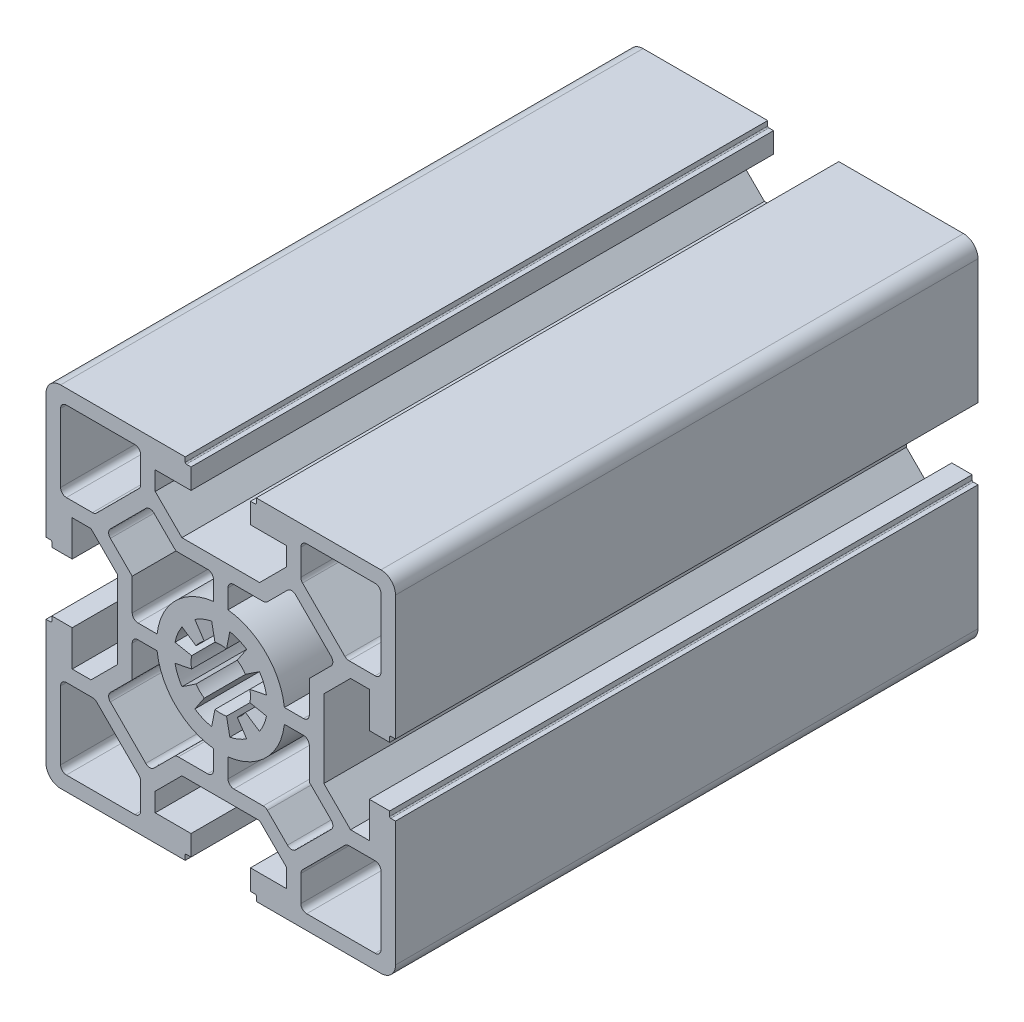
SolidWorks part; units mm, degrees
ref_plane "前视基准面" through (0, 0, 0) normal (0, 0, 1) x (1, 0, 0)
ref_plane "上视基准面" through (0, 0, 0) normal (0, 1, 0) x (1, 0, 0)
ref_plane "右视基准面" through (0, 0, 0) normal (1, 0, 0) x (0, 0, -1)
sketch "草图1" plane through (0, 0, 0) normal (0, 0, 1) x (1, 0, 0)
  line L0 (-4.4632, 29.8486) -> (-25.8632, 29.8486)
  line L1 (-28.3632, 27.3486) -> (-28.3632, 5.9486)
  line L2 (-24.8632, 13.5986) -> (-20.3827, 13.5986)
  line L3 (-19.6756, 13.8915) -> (-12.4061, 21.161)
  line L4 (-12.1132, 21.8682) -> (-12.1132, 26.3486)
  line L5 (-13.1132, 27.3486) -> (-24.8632, 27.3486)
  line L6 (-25.8632, 26.3486) -> (-25.8632, 14.5986)
  line L7 (1.6368, 17.5486) -> (-5.0323, 17.5486)
  line L8 (0.3868, 10.7773) -> (0.3868, 14.0486)
  line L9 (-0.6132, 15.0486) -> (-5.6536, 15.0486)
  line L10 (-6.3607, 15.3415) -> (-9.8183, 18.7991)
  line L11 (-16.0632, 6.5177) -> (-16.0632, -0.1514)
  line L12 (-13.5632, 7.5533) -> (-13.5632, 2.0986)
  line L13 (-12.5632, 1.0986) -> (-9.2919, 1.0986)
  line L14 (-3.4632, 25.3486) -> (-9.6132, 25.3486)
  line L15 (-23.8632, 11.0986) -> (-23.8632, 4.9486)
  line L16 (-3.4632, 28.8486) -> (-4.2632, 28.8486)
  line L17 (-4.4632, 29.0486) -> (-4.4632, 29.8486)
  line L18 (-28.3632, 5.9486) -> (-27.5632, 5.9486)
  line L19 (-27.3632, 5.7486) -> (-27.3632, 4.9486)
  line L20 (-23.8632, 11.0986) -> (-20.644, 11.0986)
  line L21 (-27.3632, 4.9486) -> (-23.8632, 4.9486)
  line L22 (-9.6132, 25.3486) -> (-9.6132, 22.1295)
  line L23 (-3.4632, 28.8486) -> (-3.4632, 25.3486)
  line L24 (-2.8077, -6.8032) -> (-1.1966, -4.3919)
  line L25 (0.0761, -7.9977) -> (0.6419, -5.1534)
  line L26 (3.1975, -7.9977) -> (2.6318, -5.1534)
  line L27 (6.0814, -6.8032) -> (4.4702, -4.3919)
  line L28 (8.2886, -4.596) -> (5.8773, -2.9848)
  line L29 (9.4831, -1.7121) -> (6.6388, -1.1464)
  line L30 (9.4831, 1.4093) -> (6.6388, 0.8436)
  line L31 (8.2886, 4.2932) -> (5.8773, 2.682)
  line L32 (6.0814, 6.5004) -> (4.4702, 4.0891)
  line L33 (3.1975, 7.6949) -> (2.6318, 4.8506)
  line L34 (0.0761, 7.6949) -> (0.6419, 4.8506)
  line L35 (-2.8077, 6.5004) -> (-1.1966, 4.0891)
  line L36 (-5.0149, 4.2932) -> (-2.6037, 2.682)
  line L37 (-6.2095, 1.4093) -> (-3.3652, 0.8436)
  line L38 (-6.2095, -1.7121) -> (-3.3652, -1.1464)
  line L39 (-5.0149, -4.596) -> (-2.6037, -2.9848)
  line L40 (-20.644, 11.0986) -> (-16.0632, 6.5177)
  line L41 (-17.3136, 11.3037) -> (-13.5632, 7.5533)
  line L42 (-9.6132, 22.1295) -> (-5.0323, 17.5486)
  line L43 (-17.3136, 12.7179) -> (-11.2325, 18.7991)
  line L44 (7.7368, 29.8486) -> (29.1368, 29.8486)
  line L45 (31.6368, 27.3486) -> (31.6368, 5.9486)
  line L46 (28.1368, 13.5986) -> (23.6564, 13.5986)
  line L47 (22.9493, 13.8915) -> (15.6797, 21.161)
  line L48 (15.3868, 21.8682) -> (15.3868, 26.3486)
  line L49 (16.3868, 27.3486) -> (28.1368, 27.3486)
  line L50 (29.1368, 26.3486) -> (29.1368, 14.5986)
  line L51 (1.6368, 17.5486) -> (8.306, 17.5486)
  line L52 (2.8868, 10.7773) -> (2.8868, 14.0486)
  line L53 (3.8868, 15.0486) -> (8.9273, 15.0486)
  line L54 (9.6344, 15.3415) -> (13.092, 18.7991)
  line L55 (19.3368, 6.5177) -> (19.3368, -0.1514)
  line L56 (16.8368, 7.5533) -> (16.8368, 2.0986)
  line L57 (15.8368, 1.0986) -> (12.5656, 1.0986)
  line L58 (6.7368, 25.3486) -> (12.8868, 25.3486)
  line L59 (27.1368, 11.0986) -> (27.1368, 4.9486)
  line L60 (6.7368, 28.8486) -> (7.5368, 28.8486)
  line L61 (7.7368, 29.0486) -> (7.7368, 29.8486)
  line L62 (31.6368, 5.9486) -> (30.8368, 5.9486)
  line L63 (30.6368, 5.7486) -> (30.6368, 4.9486)
  line L64 (27.1368, 11.0986) -> (23.9177, 11.0986)
  line L65 (30.6368, 4.9486) -> (27.1368, 4.9486)
  line L66 (12.8868, 25.3486) -> (12.8868, 22.1295)
  line L67 (6.7368, 28.8486) -> (6.7368, 25.3486)
  line L68 (23.9177, 11.0986) -> (19.3368, 6.5177)
  line L69 (20.5873, 11.3037) -> (16.8368, 7.5533)
  line L70 (12.8868, 22.1295) -> (8.306, 17.5486)
  line L71 (20.5873, 12.7179) -> (14.5062, 18.7991)
  line L72 (-4.4632, -30.1514) -> (-25.8632, -30.1514)
  line L73 (-28.3632, -27.6514) -> (-28.3632, -6.2514)
  line L74 (-24.8632, -13.9014) -> (-20.3827, -13.9014)
  line L75 (-19.6756, -14.1943) -> (-12.4061, -21.4638)
  line L76 (-12.1132, -22.171) -> (-12.1132, -26.6514)
  line L77 (-13.1132, -27.6514) -> (-24.8632, -27.6514)
  line L78 (-25.8632, -26.6514) -> (-25.8632, -14.9014)
  line L79 (1.6368, -17.8514) -> (-5.0323, -17.8514)
  line L80 (0.3868, -11.0801) -> (0.3868, -14.3514)
  line L81 (-0.6132, -15.3514) -> (-5.6536, -15.3514)
  line L82 (-6.3607, -15.6443) -> (-9.8183, -19.1019)
  line L83 (-16.0632, -6.8205) -> (-16.0632, -0.1514)
  line L84 (-13.5632, -7.8561) -> (-13.5632, -2.4014)
  line L85 (-12.5632, -1.4014) -> (-9.2919, -1.4014)
  line L86 (-3.4632, -25.6514) -> (-9.6132, -25.6514)
  line L87 (-23.8632, -11.4014) -> (-23.8632, -5.2514)
  line L88 (-3.4632, -29.1514) -> (-4.2632, -29.1514)
  line L89 (-4.4632, -29.3514) -> (-4.4632, -30.1514)
  line L90 (-28.3632, -6.2514) -> (-27.5632, -6.2514)
  line L91 (-27.3632, -6.0514) -> (-27.3632, -5.2514)
  line L92 (-23.8632, -11.4014) -> (-20.644, -11.4014)
  line L93 (-27.3632, -5.2514) -> (-23.8632, -5.2514)
  line L94 (-9.6132, -25.6514) -> (-9.6132, -22.4323)
  line L95 (-3.4632, -29.1514) -> (-3.4632, -25.6514)
  line L96 (-20.644, -11.4014) -> (-16.0632, -6.8205)
  line L97 (-17.3136, -11.6065) -> (-13.5632, -7.8561)
  line L98 (-9.6132, -22.4323) -> (-5.0323, -17.8514)
  line L99 (-17.3136, -13.0207) -> (-11.2325, -19.1019)
  line L100 (7.7368, -30.1514) -> (29.1368, -30.1514)
  line L101 (31.6368, -27.6514) -> (31.6368, -6.2514)
  line L102 (28.1368, -13.9014) -> (23.6564, -13.9014)
  line L103 (22.9493, -14.1943) -> (15.6797, -21.4638)
  line L104 (15.3868, -22.171) -> (15.3868, -26.6514)
  line L105 (16.3868, -27.6514) -> (28.1368, -27.6514)
  line L106 (29.1368, -26.6514) -> (29.1368, -14.9014)
  line L107 (1.6368, -17.8514) -> (8.306, -17.8514)
  line L108 (2.8868, -11.0801) -> (2.8868, -14.3514)
  line L109 (3.8868, -15.3514) -> (8.9273, -15.3514)
  line L110 (9.6344, -15.6443) -> (13.092, -19.1019)
  line L111 (19.3368, -6.8205) -> (19.3368, -0.1514)
  line L112 (16.8368, -7.8561) -> (16.8368, -2.4014)
  line L113 (15.8368, -1.4014) -> (12.5656, -1.4014)
  line L114 (6.7368, -25.6514) -> (12.8868, -25.6514)
  line L115 (27.1368, -11.4014) -> (27.1368, -5.2514)
  line L116 (6.7368, -29.1514) -> (7.5368, -29.1514)
  line L117 (7.7368, -29.3514) -> (7.7368, -30.1514)
  line L118 (31.6368, -6.2514) -> (30.8368, -6.2514)
  line L119 (30.6368, -6.0514) -> (30.6368, -5.2514)
  line L120 (27.1368, -11.4014) -> (23.9177, -11.4014)
  line L121 (30.6368, -5.2514) -> (27.1368, -5.2514)
  line L122 (12.8868, -25.6514) -> (12.8868, -22.4323)
  line L123 (6.7368, -29.1514) -> (6.7368, -25.6514)
  line L124 (23.9177, -11.4014) -> (19.3368, -6.8205)
  line L125 (20.5873, -11.6065) -> (16.8368, -7.8561)
  line L126 (12.8868, -22.4323) -> (8.306, -17.8514)
  line L127 (20.5873, -13.0207) -> (14.5062, -19.1019)
  arc A0 (-25.8632, 29.8486) -> (-28.3632, 27.3486) centre (-25.8632, 27.3486) ccw
  arc A1 (-20.3827, 13.5986) -> (-19.6756, 13.8915) centre (-20.3827, 14.5986) ccw
  arc A2 (-12.4061, 21.161) -> (-12.1132, 21.8682) centre (-13.1132, 21.8682) ccw
  arc A3 (-12.1132, 26.3486) -> (-13.1132, 27.3486) centre (-13.1132, 26.3486) ccw
  arc A4 (-24.8632, 27.3486) -> (-25.8632, 26.3486) centre (-24.8632, 26.3486) ccw
  arc A5 (-25.8632, 14.5986) -> (-24.8632, 13.5986) centre (-24.8632, 14.5986) ccw
  arc A6 (0.3868, 14.0486) -> (-0.6132, 15.0486) centre (-0.6132, 14.0486) ccw
  arc A7 (-6.3607, 15.3415) -> (-5.6536, 15.0486) centre (-5.6536, 16.0486) ccw
  arc A8 (-13.5632, 2.0986) -> (-12.5632, 1.0986) centre (-12.5632, 2.0986) ccw
  arc A9 (-4.4632, 29.0486) -> (-4.2632, 28.8486) centre (-4.2632, 29.0486) ccw
  arc A10 (-27.3632, 5.7486) -> (-27.5632, 5.9486) centre (-27.5632, 5.7486) ccw
  arc A11 (0.6419, -5.1534) -> (2.6318, -5.1534) centre (1.6368, -0.1514) ccw
  arc A12 (4.4702, -4.3919) -> (5.8773, -2.9848) centre (1.6368, -0.1514) ccw
  arc A13 (6.6388, -1.1464) -> (6.6388, 0.8436) centre (1.6368, -0.1514) ccw
  arc A14 (5.8773, 2.682) -> (4.4702, 4.0891) centre (1.6368, -0.1514) ccw
  arc A15 (2.6318, 4.8506) -> (0.6419, 4.8506) centre (1.6368, -0.1514) ccw
  arc A16 (-1.1966, 4.0891) -> (-2.6037, 2.682) centre (1.6368, -0.1514) ccw
  arc A17 (-3.3652, 0.8436) -> (-3.3652, -1.1464) centre (1.6368, -0.1514) ccw
  arc A18 (-2.6037, -2.9848) -> (-1.1966, -4.3919) centre (1.6368, -0.1514) ccw
  arc A19 (-2.8077, -6.8032) -> (0.0761, -7.9977) centre (1.6368, -0.1514) ccw
  arc A20 (3.1975, -7.9977) -> (6.0814, -6.8032) centre (1.6368, -0.1514) ccw
  arc A21 (8.2886, -4.596) -> (9.4831, -1.7121) centre (1.6368, -0.1514) ccw
  arc A22 (9.4831, 1.4093) -> (8.2886, 4.2932) centre (1.6368, -0.1514) ccw
  arc A23 (6.0814, 6.5004) -> (3.1975, 7.6949) centre (1.6368, -0.1514) ccw
  arc A24 (0.0761, 7.6949) -> (-2.8077, 6.5004) centre (1.6368, -0.1514) ccw
  arc A25 (-5.0149, 4.2932) -> (-6.2095, 1.4093) centre (1.6368, -0.1514) ccw
  arc A26 (-6.2095, -1.7121) -> (-5.0149, -4.596) centre (1.6368, -0.1514) ccw
  arc A27 (-9.2919, -1.4014) -> (0.3868, -11.0801) centre (1.6368, -0.1514) ccw
  arc A28 (2.8868, -11.0801) -> (12.5656, -1.4014) centre (1.6368, -0.1514) ccw
  arc A29 (12.5656, 1.0986) -> (2.8868, 10.7773) centre (1.6368, -0.1514) ccw
  arc A30 (0.3868, 10.7773) -> (-9.2919, 1.0986) centre (1.6368, -0.1514) ccw
  arc A31 (-9.8183, 18.7991) -> (-11.2325, 18.7991) centre (-10.5254, 18.092) ccw
  arc A32 (-17.3136, 12.7179) -> (-17.3136, 11.3037) centre (-16.6065, 12.0108) ccw
  arc A33 (31.6368, 27.3486) -> (29.1368, 29.8486) centre (29.1368, 27.3486) ccw
  arc A34 (22.9493, 13.8915) -> (23.6564, 13.5986) centre (23.6564, 14.5986) ccw
  arc A35 (15.3868, 21.8682) -> (15.6797, 21.161) centre (16.3868, 21.8682) ccw
  arc A36 (16.3868, 27.3486) -> (15.3868, 26.3486) centre (16.3868, 26.3486) ccw
  arc A37 (29.1368, 26.3486) -> (28.1368, 27.3486) centre (28.1368, 26.3486) ccw
  arc A38 (28.1368, 13.5986) -> (29.1368, 14.5986) centre (28.1368, 14.5986) ccw
  arc A39 (3.8868, 15.0486) -> (2.8868, 14.0486) centre (3.8868, 14.0486) ccw
  arc A40 (8.9273, 15.0486) -> (9.6344, 15.3415) centre (8.9273, 16.0486) ccw
  arc A41 (15.8368, 1.0986) -> (16.8368, 2.0986) centre (15.8368, 2.0986) ccw
  arc A42 (7.5368, 28.8486) -> (7.7368, 29.0486) centre (7.5368, 29.0486) ccw
  arc A43 (30.8368, 5.9486) -> (30.6368, 5.7486) centre (30.8368, 5.7486) ccw
  arc A44 (14.5062, 18.7991) -> (13.092, 18.7991) centre (13.7991, 18.092) ccw
  arc A45 (20.5873, 11.3037) -> (20.5873, 12.7179) centre (19.8802, 12.0108) ccw
  arc A46 (-28.3632, -27.6514) -> (-25.8632, -30.1514) centre (-25.8632, -27.6514) ccw
  arc A47 (-19.6756, -14.1943) -> (-20.3827, -13.9014) centre (-20.3827, -14.9014) ccw
  arc A48 (-12.1132, -22.171) -> (-12.4061, -21.4638) centre (-13.1132, -22.171) ccw
  arc A49 (-13.1132, -27.6514) -> (-12.1132, -26.6514) centre (-13.1132, -26.6514) ccw
  arc A50 (-25.8632, -26.6514) -> (-24.8632, -27.6514) centre (-24.8632, -26.6514) ccw
  arc A51 (-24.8632, -13.9014) -> (-25.8632, -14.9014) centre (-24.8632, -14.9014) ccw
  arc A52 (-0.6132, -15.3514) -> (0.3868, -14.3514) centre (-0.6132, -14.3514) ccw
  arc A53 (-5.6536, -15.3514) -> (-6.3607, -15.6443) centre (-5.6536, -16.3514) ccw
  arc A54 (-12.5632, -1.4014) -> (-13.5632, -2.4014) centre (-12.5632, -2.4014) ccw
  arc A55 (-4.2632, -29.1514) -> (-4.4632, -29.3514) centre (-4.2632, -29.3514) ccw
  arc A56 (-27.5632, -6.2514) -> (-27.3632, -6.0514) centre (-27.5632, -6.0514) ccw
  arc A61 (-11.2325, -19.1019) -> (-9.8183, -19.1019) centre (-10.5254, -18.3948) ccw
  arc A62 (-17.3136, -11.6065) -> (-17.3136, -13.0207) centre (-16.6065, -12.3136) ccw
  arc A63 (29.1368, -30.1514) -> (31.6368, -27.6514) centre (29.1368, -27.6514) ccw
  arc A64 (23.6564, -13.9014) -> (22.9493, -14.1943) centre (23.6564, -14.9014) ccw
  arc A65 (15.6797, -21.4638) -> (15.3868, -22.171) centre (16.3868, -22.171) ccw
  arc A66 (15.3868, -26.6514) -> (16.3868, -27.6514) centre (16.3868, -26.6514) ccw
  arc A67 (28.1368, -27.6514) -> (29.1368, -26.6514) centre (28.1368, -26.6514) ccw
  arc A68 (29.1368, -14.9014) -> (28.1368, -13.9014) centre (28.1368, -14.9014) ccw
  arc A69 (2.8868, -14.3514) -> (3.8868, -15.3514) centre (3.8868, -14.3514) ccw
  arc A70 (9.6344, -15.6443) -> (8.9273, -15.3514) centre (8.9273, -16.3514) ccw
  arc A71 (16.8368, -2.4014) -> (15.8368, -1.4014) centre (15.8368, -2.4014) ccw
  arc A72 (7.7368, -29.3514) -> (7.5368, -29.1514) centre (7.5368, -29.3514) ccw
  arc A73 (30.6368, -6.0514) -> (30.8368, -6.2514) centre (30.8368, -6.0514) ccw
  arc A74 (13.092, -19.1019) -> (14.5062, -19.1019) centre (13.7991, -18.3948) ccw
  arc A75 (20.5873, -13.0207) -> (20.5873, -11.6065) centre (19.8802, -12.3136) ccw
extrude "凸台-拉伸1" add sketch "草图1" along normal blind 100
